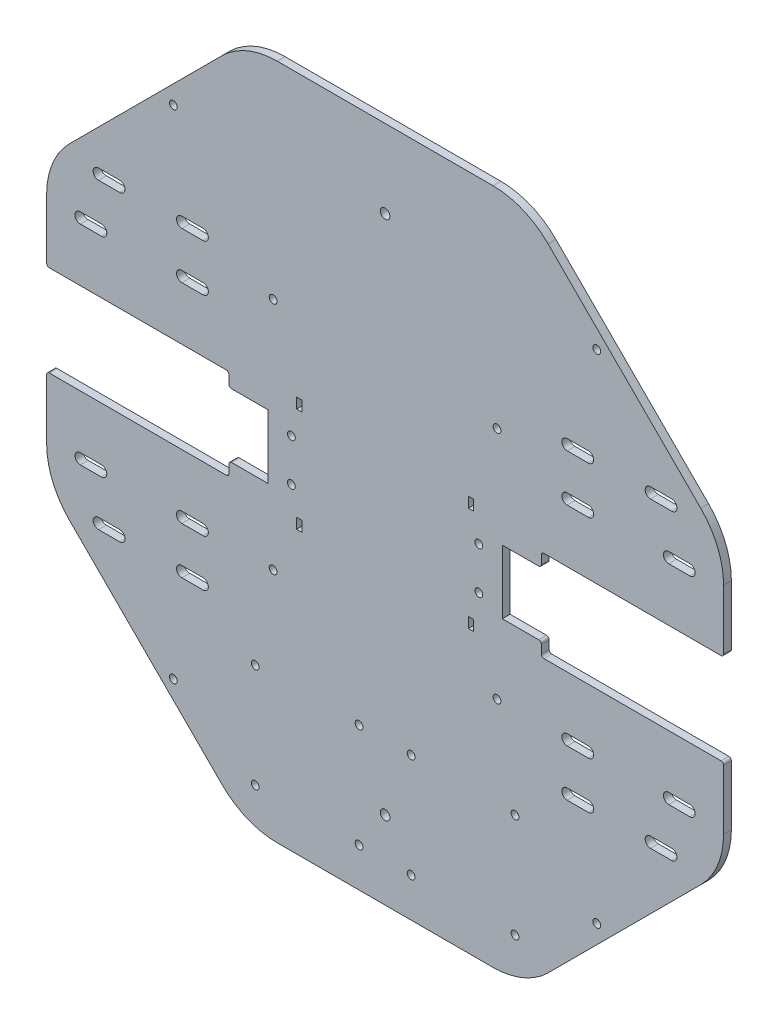
SolidWorks part; units mm, degrees
ref_plane "Front Plane" through (0, 0, 0) normal (0, 0, 1) x (1, 0, 0)
ref_plane "Top Plane" through (0, 0, 0) normal (0, 1, 0) x (1, 0, 0)
ref_plane "Right Plane" through (0, 0, 0) normal (1, 0, 0) x (0, 0, -1)
sketch "Sketch1" plane through (0, 0, 0) normal (0, 0, 1) x (1, 0, 0)
  line L0 (-179.569, 0) -> (179.66, 0) construction
  line L9 (0, 178.9146) -> (0, -184.198) construction
  line L10 (130, 17.5) -> (130, 41.4214)
  line L15 (121.2132, 62.6346) -> (62.6346, 121.2132)
  line L16 (41.4214, 130) -> (-41.4214, 130)
  line L17 (-62.6346, 121.2132) -> (-121.2132, 62.6346)
  line L24 (-130, 41.4214) -> (-130, 17.5)
  line L25 (-121.2132, -62.6346) -> (-62.6346, -121.2132)
  line L26 (-41.4214, -130) -> (41.4214, -130)
  line L27 (62.6346, -121.2132) -> (121.2132, -62.6346)
  line L28 (130, -41.4214) -> (130, -17.5)
  line L29 (130, 17.5) -> (60, 17.5)
  line L31 (130, -17.5) -> (60, -17.5)
  line L32 (60, 17.5) -> (60, 12.25)
  line L33 (-130, -17.5) -> (-60, -17.5)
  line L35 (-130, 17.5) -> (-60, 17.5)
  line L36 (-130, -17.5) -> (-130, -41.4214)
  line L41 (45, 12.25) -> (45, -12.25)
  line L53 (69.925, 40.05) -> (78.075, 40.05) construction
  line L54 (69.925, 42.0875) -> (78.075, 42.0875)
  line L55 (69.925, 38.0125) -> (78.075, 38.0125)
  line L56 (69.925, 58.1) -> (78.075, 58.1) construction
  line L57 (69.925, 60.1375) -> (78.075, 60.1375)
  line L58 (69.925, 56.0625) -> (78.075, 56.0625)
  line L59 (101.925, 58.1) -> (110.075, 58.1) construction
  line L60 (101.925, 60.1375) -> (110.075, 60.1375)
  line L61 (101.925, 56.0625) -> (110.075, 56.0625)
  line L62 (-69.925, 58.1) -> (-78.075, 58.1) construction
  line L65 (108.925, 40.05) -> (117.075, 40.05) construction
  line L66 (108.925, 42.0875) -> (117.075, 42.0875)
  line L67 (108.925, 38.0125) -> (117.075, 38.0125)
  line L68 (-101.925, -58.1) -> (-110.075, -58.1) construction
  line L71 (-69.925, 60.1375) -> (-78.075, 60.1375)
  line L72 (-69.925, 56.0625) -> (-78.075, 56.0625)
  line L73 (-101.925, 58.1) -> (-110.075, 58.1) construction
  line L74 (-101.925, 60.1375) -> (-110.075, 60.1375)
  line L75 (-101.925, 56.0625) -> (-110.075, 56.0625)
  line L76 (-108.925, 40.05) -> (-117.075, 40.05) construction
  line L77 (-108.925, 42.0875) -> (-117.075, 42.0875)
  line L78 (-108.925, 38.0125) -> (-117.075, 38.0125)
  line L79 (-69.925, 40.05) -> (-78.075, 40.05) construction
  line L80 (-69.925, 42.0875) -> (-78.075, 42.0875)
  line L81 (-69.925, 38.0125) -> (-78.075, 38.0125)
  line L82 (101.925, -58.1) -> (110.075, -58.1) construction
  line L83 (101.925, -60.1375) -> (110.075, -60.1375)
  line L84 (101.925, -56.0625) -> (110.075, -56.0625)
  line L85 (69.925, -58.1) -> (78.075, -58.1) construction
  line L86 (69.925, -60.1375) -> (78.075, -60.1375)
  line L87 (69.925, -56.0625) -> (78.075, -56.0625)
  line L88 (69.925, -40.05) -> (78.075, -40.05) construction
  line L89 (69.925, -42.0875) -> (78.075, -42.0875)
  line L90 (69.925, -38.0125) -> (78.075, -38.0125)
  line L91 (108.925, -40.05) -> (117.075, -40.05) construction
  line L92 (108.925, -42.0875) -> (117.075, -42.0875)
  line L93 (108.925, -38.0125) -> (117.075, -38.0125)
  line L94 (-101.925, -60.1375) -> (-110.075, -60.1375)
  line L95 (-101.925, -56.0625) -> (-110.075, -56.0625)
  line L96 (-69.925, -58.1) -> (-78.075, -58.1) construction
  line L97 (-69.925, -60.1375) -> (-78.075, -60.1375)
  line L98 (-69.925, -56.0625) -> (-78.075, -56.0625)
  line L99 (-69.925, -40.05) -> (-78.075, -40.05) construction
  line L100 (-69.925, -42.0875) -> (-78.075, -42.0875)
  line L101 (-69.925, -38.0125) -> (-78.075, -38.0125)
  line L102 (-108.925, -40.05) -> (-117.075, -40.05) construction
  line L103 (-108.925, -42.0875) -> (-117.075, -42.0875)
  line L104 (-108.925, -38.0125) -> (-117.075, -38.0125)
  line L107 (60, 12.25) -> (45, 12.25)
  line L108 (60, -12.25) -> (45, -12.25)
  line L109 (60, -17.5) -> (60, -12.25)
  line L110 (-60, 17.5) -> (-60, 12.25)
  line L111 (-60, -17.5) -> (-60, -12.25)
  line L112 (-60, -12.25) -> (-45, -12.25)
  line L113 (-60, 12.25) -> (-45, 12.25)
  line L114 (-45, 12.25) -> (-45, -12.25)
  arc A0 (128.8167, 17.5) -> (-128.8167, 17.5) centre (0, 0) ccw construction
  arc A1 (41.4214, -130) -> (62.6346, -121.2132) centre (41.4214, -100) ccw
  arc A2 (-62.6346, -121.2132) -> (-41.4214, -130) centre (-41.4214, -100) ccw
  arc A3 (121.2132, -62.6346) -> (130, -41.4214) centre (100, -41.4214) ccw
  arc A4 (121.2132, 62.6346) -> (130, 41.4214) centre (100, 41.4214) cw
  arc A5 (-130, -41.4214) -> (-121.2132, -62.6346) centre (-100, -41.4214) ccw
  arc A6 (62.6346, 121.2132) -> (41.4214, 130) centre (41.4214, 100) ccw
  arc A7 (-41.4214, 130) -> (-62.6346, 121.2132) centre (-41.4214, 100) ccw
  arc A8 (-121.2132, 62.6346) -> (-130, 41.4214) centre (-100, 41.4214) ccw
  arc A9 (-128.8167, -17.5) -> (128.8167, -17.5) centre (0, 0) ccw construction
  circle A10 centre (0, 100) radius 1.85
  circle A11 centre (0, -100) radius 1.85
  arc A16 (69.925, 42.0875) -> (69.925, 38.0125) centre (69.925, 40.05) ccw
  arc A17 (78.075, 38.0125) -> (78.075, 42.0875) centre (78.075, 40.05) ccw
  arc A18 (69.925, 60.1375) -> (69.925, 56.0625) centre (69.925, 58.1) ccw
  arc A19 (78.075, 56.0625) -> (78.075, 60.1375) centre (78.075, 58.1) ccw
  arc A20 (101.925, 60.1375) -> (101.925, 56.0625) centre (101.925, 58.1) ccw
  arc A21 (110.075, 56.0625) -> (110.075, 60.1375) centre (110.075, 58.1) ccw
  arc A24 (108.925, 42.0875) -> (108.925, 38.0125) centre (108.925, 40.05) ccw
  arc A25 (117.075, 38.0125) -> (117.075, 42.0875) centre (117.075, 40.05) ccw
  arc A28 (-69.925, 60.1375) -> (-69.925, 56.0625) centre (-69.925, 58.1) cw
  arc A29 (-78.075, 56.0625) -> (-78.075, 60.1375) centre (-78.075, 58.1) cw
  arc A30 (-101.925, 60.1375) -> (-101.925, 56.0625) centre (-101.925, 58.1) cw
  arc A31 (-110.075, 56.0625) -> (-110.075, 60.1375) centre (-110.075, 58.1) cw
  arc A32 (-108.925, 42.0875) -> (-108.925, 38.0125) centre (-108.925, 40.05) cw
  arc A33 (-117.075, 38.0125) -> (-117.075, 42.0875) centre (-117.075, 40.05) cw
  arc A34 (-69.925, 42.0875) -> (-69.925, 38.0125) centre (-69.925, 40.05) cw
  arc A35 (-78.075, 38.0125) -> (-78.075, 42.0875) centre (-78.075, 40.05) cw
  arc A36 (101.925, -60.1375) -> (101.925, -56.0625) centre (101.925, -58.1) cw
  arc A37 (110.075, -56.0625) -> (110.075, -60.1375) centre (110.075, -58.1) cw
  arc A38 (69.925, -60.1375) -> (69.925, -56.0625) centre (69.925, -58.1) cw
  arc A39 (78.075, -56.0625) -> (78.075, -60.1375) centre (78.075, -58.1) cw
  arc A40 (69.925, -42.0875) -> (69.925, -38.0125) centre (69.925, -40.05) cw
  arc A41 (78.075, -38.0125) -> (78.075, -42.0875) centre (78.075, -40.05) cw
  arc A42 (108.925, -42.0875) -> (108.925, -38.0125) centre (108.925, -40.05) cw
  arc A43 (117.075, -38.0125) -> (117.075, -42.0875) centre (117.075, -40.05) cw
  arc A44 (-101.925, -60.1375) -> (-101.925, -56.0625) centre (-101.925, -58.1) ccw
  arc A45 (-110.075, -56.0625) -> (-110.075, -60.1375) centre (-110.075, -58.1) ccw
  arc A46 (-69.925, -60.1375) -> (-69.925, -56.0625) centre (-69.925, -58.1) ccw
  arc A47 (-78.075, -56.0625) -> (-78.075, -60.1375) centre (-78.075, -58.1) ccw
  arc A48 (-69.925, -42.0875) -> (-69.925, -38.0125) centre (-69.925, -40.05) ccw
  arc A49 (-78.075, -38.0125) -> (-78.075, -42.0875) centre (-78.075, -40.05) ccw
  arc A50 (-108.925, -42.0875) -> (-108.925, -38.0125) centre (-108.925, -40.05) ccw
  arc A51 (-117.075, -38.0125) -> (-117.075, -42.0875) centre (-117.075, -40.05) ccw
  circle A52 centre (36, 8.1) radius 1.5
  circle A54 centre (36, -8.1) radius 1.5
  circle A55 centre (-36, -8.1) radius 1.5
  circle A56 centre (-36, 8.1) radius 1.5
  point P49 (45, 0)
  point P63 (74, 58.1)
  point P71 (74, 40.05)
  point P78 (106, 58.1)
  point P89 (-74, 58.1)
  point P92 (113, 40.05)
  point P101 (-106, -58.1)
  point P110 (-106, 58.1)
  point P117 (-113, 40.05)
  point P124 (-74, 40.05)
  point P131 (106, -58.1)
  point P138 (74, -58.1)
  point P145 (74, -40.05)
  point P152 (113, -40.05)
  point P159 (-74, -58.1)
  point P166 (-74, -40.05)
  point P173 (-113, -40.05)
  dimension "D3" = 70
  dimension "D4" = 35
  dimension "D2" = 30
  dimension "D7" = 3.7
  dimension "D14" = 18.05
  dimension "D15" = 40.05
  dimension "D16" = 18.05
  dimension "D17" = 40.05
  dimension "D22" = 2.0375
  dimension "D26" = 2.0375
  dimension "D27" = 2.0375
  dimension "D28" = 2.0375
  dimension "D30" = 9
  dimension "D12" = 3
  dimension "D1" = 260
  dimension "D5" = 112.5
  dimension "D6" = 30
  dimension "D8" = 5.25
  dimension "D9" = 15
  dimension "D10" = 24.5
  dimension "D11" = 5.25
  dimension "D13" = 8.1
  dimension "D18" = 17
  dimension "D19" = 39
  dimension "D20" = 32
  dimension "D21" = 8.15
  dimension "D23" = 8.15
  dimension "D24" = 8.15
  dimension "D25" = 8.15
  dimension "D29" = 56
extrude "Boss-Extrude1" add sketch "Sketch1" along normal blind 3
sketch "Sketch2" plane through (0, 0, 3) normal (0, 0, 1) x (1, 0, 0)
  line L0 (0, 0) -> (0, 15.3291) construction
  line L1 (45, -12.25) -> (45, 12.25) construction
  line L3 (34, -18) -> (34, -22)
  line L4 (0, 0) -> (-14.4964, 0) construction
  line L5 (-130, 17.5) -> (-60, 17.5) construction
  line L8 (34, 22) -> (32, 22)
  line L13 (-34, 18) -> (-32, 18)
  line L14 (-34, 18) -> (-34, 22)
  line L15 (-34, 22) -> (-32, 22)
  line L16 (-32, 18) -> (-32, 22)
  line L17 (-34, 18) -> (-32, 22) construction
  line L18 (-34, 22) -> (-32, 18) construction
  line L19 (32, 18) -> (32, 22)
  line L20 (34, 18) -> (32, 18)
  line L21 (34, 18) -> (34, 22)
  line L22 (34, -18) -> (32, -18)
  line L23 (32, -18) -> (32, -22)
  line L24 (34, -22) -> (32, -22)
  line L25 (-34, -22) -> (-32, -22)
  line L26 (-32, -18) -> (-32, -22)
  line L27 (-34, -18) -> (-32, -18)
  line L28 (-34, -18) -> (-34, -22)
  line L29 (-41.4214, -130) -> (41.4214, -130) construction
  line L32 (-49.9, -75.1) -> (-49.9, -115) construction
  line L33 (-49.9, -75.1) -> (-10, -75.1) construction
  line L34 (-10, -75.1) -> (-10, -115) construction
  line L35 (-49.9, -115) -> (-10, -115) construction
  line L36 (0, -29.2307) -> (0, -143.1735) construction
  line L37 (10, -75.1) -> (10, -115) construction
  line L38 (49.9, -75.1) -> (10, -75.1) construction
  line L39 (49.9, -75.1) -> (49.9, -115) construction
  line L40 (49.9, -115) -> (10, -115) construction
  circle A10 centre (-10, -75.1) radius 1.5
  circle A11 centre (-49.9, -75.1) radius 1.5
  circle A12 centre (-10, -115) radius 1.5
  circle A13 centre (-49.9, -115) radius 1.5
  circle A14 centre (10, -75.1) radius 1.5
  circle A15 centre (49.9, -75.1) radius 1.5
  circle A16 centre (49.9, -115) radius 1.5
  circle A17 centre (10, -115) radius 1.5
  point P12 (-33, 20)
  dimension "D6" = 33
  dimension "D10" = 20
  dimension "D4" = 2
  dimension "D17" = 3
  dimension "D19" = 15
  dimension "D5" = 4
  dimension "D18" = 39.9
  dimension "D20" = 10
extrude "Cut-Extrude1" cut sketch "Sketch2" against normal blind 10
sketch "Just_Show" plane through (0, 0, 3) normal (0, 0, 1) x (1, 0, 0)
  line L0 (-56, -69) -> (-56, -120) construction
  line L1 (-56, -120) -> (-5, -120) construction
  line L2 (-5, -120) -> (-5, -69) construction
  line L3 (-5, -69) -> (-56, -69) construction
  line L4 (0, 170.5016) -> (0, -164.4984) construction
  line L5 (-220.8645, 0) -> (179.1355, 0) construction
  line L6 (-41.4214, -130) -> (41.4214, -130) construction
  line L7 (5, -120) -> (5, -69) construction
  line L8 (56, -120) -> (5, -120) construction
  line L9 (56, -69) -> (56, -120) construction
  line L10 (5, -69) -> (56, -69) construction
  dimension "D1" = 51
  dimension "D2" = 10
  dimension "D3" = 5
fillet "Fillet1" radius 1 6 edges at (60, -17.5, 1.5) (60, 17.5, 1.5) (60, 12.25, 1.5) (130, 17.5, 1.5) (130, -17.5, 1.5) (60, -12.25, 1.5)
fillet "Fillet2" radius 1 6 edges at (-60, -17.5, 1.5) (-60, 17.5, 1.5) (-60, 12.25, 1.5) (-60, -12.25, 1.5) (-130, -17.5, 1.5) (-130, 17.5, 1.5)
sketch "Sketch3" plane through (0, 0, 3) normal (0, 0, 1) x (1, 0, 0)
  line L0 (-43, 50) -> (-43, -40) construction
  line L1 (-130, 41.4214) -> (-130, 18.5) construction
  line L2 (41.4214, 130) -> (-41.4214, 130) construction
  line L5 (43, 50) -> (43, -55.1681) construction
  line L6 (130, 18.5) -> (130, 41.4214) construction
  line L7 (-91.9239, -91.9239) -> (-88.0714, -88.0714) construction
  line L8 (-121.2132, -62.6346) -> (-62.6346, -121.2132) construction
  line L9 (91.9239, -91.9239) -> (87.1881, -87.1881) construction
  line L10 (62.6346, -121.2132) -> (121.2132, -62.6346) construction
  line L11 (91.9239, 91.9239) -> (88.5561, 88.5561) construction
  line L12 (121.2132, 62.6346) -> (62.6346, 121.2132) construction
  line L13 (-91.9239, 91.9239) -> (-82.7494, 82.7494) construction
  line L14 (-62.6346, 121.2132) -> (-121.2132, 62.6346) construction
  circle A0 centre (-43, 50) radius 1.5
  circle A1 centre (-43, -40) radius 1.5
  circle A3 centre (43, -40) radius 1.5
  circle A4 centre (43, 50) radius 1.5
  circle A5 centre (-81.3173, 95.4594) radius 1.5
  circle A6 centre (81.3173, 95.4594) radius 1.5
  circle A7 centre (81.3173, -95.4594) radius 1.5
  circle A8 centre (-81.3173, -95.4594) radius 1.5
  dimension "D1" = 3
  dimension "D11" = 3
  dimension "D2" = 90
  dimension "D3" = 87
  dimension "D4" = 80
  dimension "D7" = 87
  dimension "D8" = 90
  dimension "D9" = 80
  dimension "D10" = 10
  dimension "D12" = 5
  dimension "D13" = 5
  dimension "D14" = 10
  dimension "D15" = 10
  dimension "D16" = 5
  dimension "D17" = 10
  dimension "D18" = 5
extrude "Cut-Extrude2" cut sketch "Sketch3" against normal blind 10
